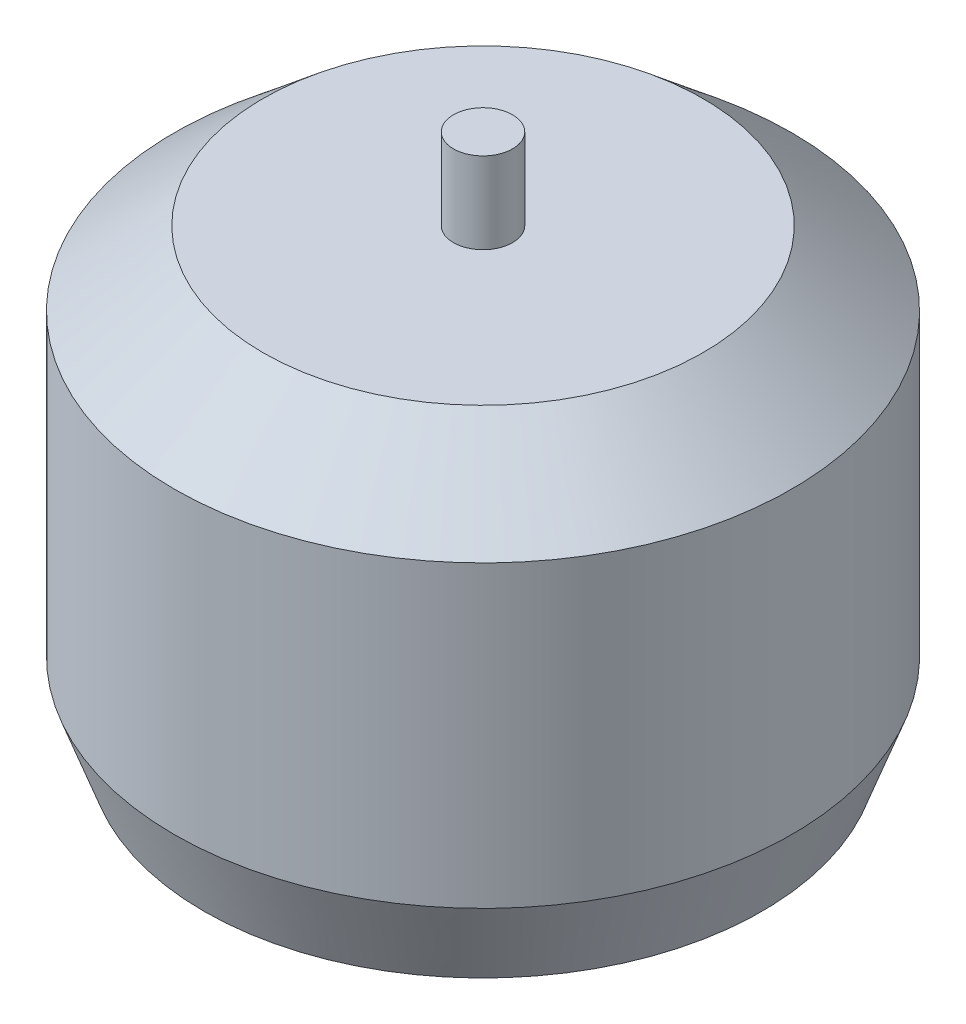
SolidWorks part; units mm, degrees
ref_plane "Front Plane" through (0, 0, 0) normal (0, 0, 1) x (1, 0, 0)
ref_plane "Top Plane" through (0, 0, 0) normal (0, 1, 0) x (1, 0, 0)
ref_plane "Right Plane" through (0, 0, 0) normal (1, 0, 0) x (0, 0, -1)
sketch "Sketch1" plane through (0, 0, 0) normal (0, 1, 0) x (1, 0, 0)
  circle A0 centre (-5.6491, -5.3281) radius 20.9
  dimension "D1" = 41.8
extrude "Boss-Extrude1" add sketch "Sketch1" along normal blind 30.75
chamfer "Chamfer1" distance 5 distance2 6 1 edges at (-5.6491, 30.75, 26.2281)
chamfer "Chamfer2" distance 2 angle 70 1 edges at (-5.6491, 0, 26.2281)
sketch "Sketch2" plane through (0, 30.75, 0) normal (0, 1, 0) x (1, 0, 0)
  circle A0 centre (-5.6491, -5.3281) radius 2
  circle A1 centre (-5.6491, -5.3281) radius 14.9 construction
  dimension "D1" = 4
  dimension "D2" = 0
  dimension "D3" = 0
extrude "Boss-Extrude2" add sketch "Sketch2" along normal blind 5.5
sketch "Sketch3" plane through (0, 0, 0) normal (0, -1, 0) x (1, 0, 0)
  circle A0 centre (-5.6491, 5.3281) radius 4
  circle A1 centre (-5.6491, 5.3281) radius 18.9 construction
  dimension "D1" = 8
  dimension "D2" = 0
extrude "Boss-Extrude3" add sketch "Sketch3" along normal blind 2.55 contours A0
sketch "Sketch4" plane through (0, 0, 0) normal (0, -1, 0) x (1, 0, 0)
  line L1 (19.434, 5.3281) -> (-5.6491, 5.3281) construction
  circle A0 centre (-5.9087, 17.486) radius 4
  circle A1 centre (-5.9087, -6.8299) radius 4
  circle A2 centre (-17.807, 5.5877) radius 4
  circle A3 centre (5.9897, 5.5877) radius 4
  circle A4 centre (-12.3666, 12.0456) radius 1
  circle A5 centre (1.0685, -1.3894) radius 1
  circle A6 centre (-11.3059, -0.3288) radius 1
  circle A7 centre (0.0078, 10.9849) radius 1
  circle A8 centre (-14.4879, -3.5107) radius 1
  circle A9 centre (3.1898, 14.1669) radius 1
  dimension "D1" = 8
  dimension "D2" = 2
  dimension "D4" = 2
  dimension "D3" = 9.5
  dimension "D5" = 8
  dimension "D6" = 12.5
extrude "Cut-Extrude1" cut sketch "Sketch4" against normal blind 1.5875
